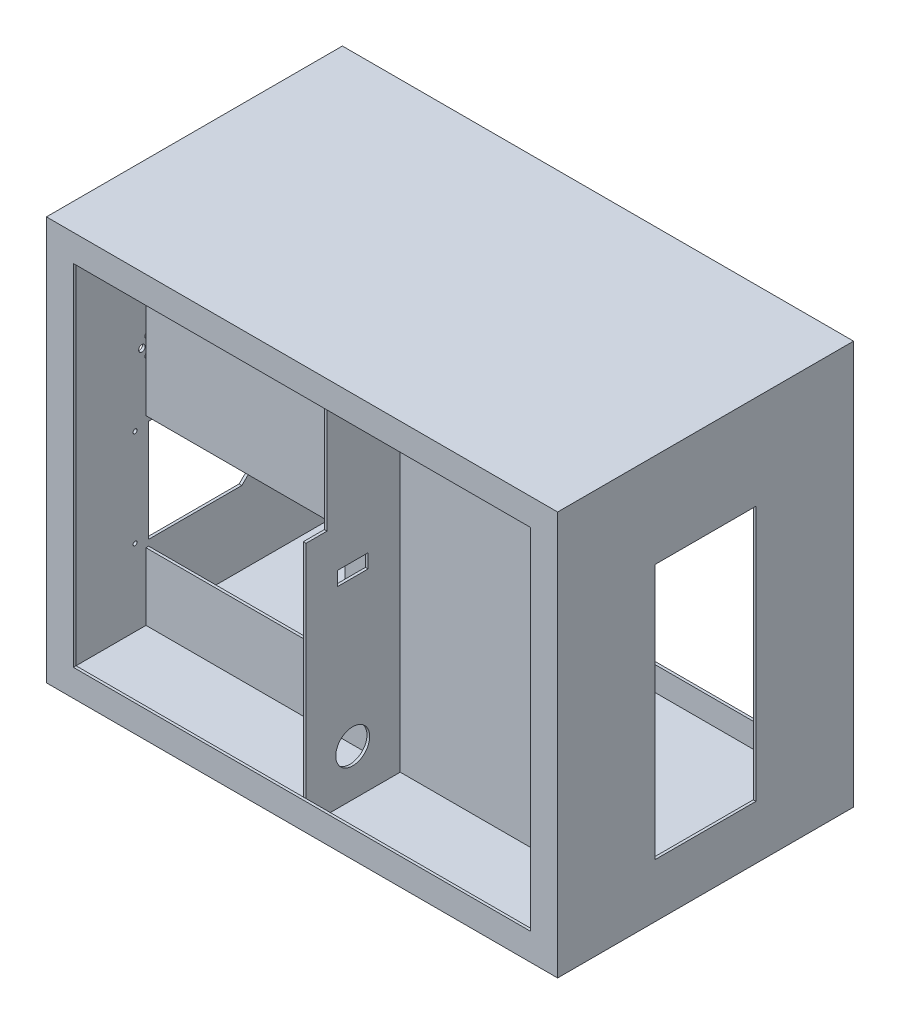
SolidWorks part; units mm, degrees
material "Acero al carbono no aleado"
ref_plane "Alzado" through (0, 0, 0) normal (0, 0, 1) x (1, 0, 0)
ref_plane "Planta" through (0, 0, 0) normal (0, 1, 0) x (1, 0, 0)
ref_plane "Vista lateral" through (0, 0, 0) normal (1, 0, 0) x (0, 0, -1)
sketch "Croquis1" plane through (0, 0, 0) normal (0, 0, 1) x (1, 0, 0)
  line L1 (190, -150) -> (-190, -150)
  line L2 (190, -150) -> (190, 150)
  line L3 (190, 150) -> (-190, 150)
  line L4 (-190, -150) -> (-190, 150)
  line L5 (190, -150) -> (-190, 150) construction
  line L6 (190, 150) -> (-190, -150) construction
  point P0 (0, 0)
  dimension "D1" = 380
  dimension "D2" = 300
extrude "Saliente-Extruir1" add sketch "Croquis1" along normal blind 220
sketch "Croquis2" plane through (0, 0, 220) normal (0, 0, 1) x (1, 0, 0)
  line L1 (-170, -130) -> (170, -130)
  line L2 (-170, -130) -> (-170, 130)
  line L3 (-170, 130) -> (170, 130)
  line L4 (170, -130) -> (170, 130)
  line L5 (-170, -130) -> (170, 130) construction
  line L6 (-170, 130) -> (170, -130) construction
  point P0 (0, 0)
  dimension "D1" = 340
  dimension "D2" = 260
extrude "Cortar-Extruir1" cut sketch "Croquis2" against normal through all
sketch "Croquis3" plane through (190, 0, 0) normal (1, 0, 0) x (0, 0, -1)
  line L0 (-220, -150) -> (0, -150) construction
  line L1 (-147.5, 80) -> (-72.5, 80)
  line L2 (-147.5, 80) -> (-147.5, -110)
  line L3 (-147.5, -110) -> (-72.5, -110)
  line L4 (-72.5, 80) -> (-72.5, -110)
  line L5 (-147.5, 80) -> (-72.5, -110) construction
  line L6 (-147.5, -110) -> (-72.5, 80) construction
  line L7 (-220, 150) -> (0, 150) construction
  point P0 (-110, -15)
  point P8 (-110, -150)
  dimension "D1" = 75
  dimension "D2" = 70
  dimension "D3" = 40
extrude "Cortar-Extruir2" cut sketch "Croquis3" against normal blind 220
sketch "Croquis4" plane through (-190, 0, 0) normal (-1, 0, 0) x (0, 0, 1)
  line L0 (20.7709, 67.1061) -> (23.2287, 61.2188)
  line L1 (22.0366, 127.5153) -> (42.2872, 127.5153)
  line L2 (22.0366, 127.5153) -> (22.0366, 99.6708)
  line L3 (22.0366, 99.6708) -> (42.2872, 99.6708)
  line L4 (42.2872, 127.5153) -> (42.2872, 99.6708)
  line L5 (154.045, 32.5908) -> (133.2882, 68.5426) construction
  line L6 (133.2882, 68.5426) -> (91.7745, 68.5426) construction
  line L7 (91.7745, 68.5426) -> (71.0177, 32.5908) construction
  line L8 (71.0177, 32.5908) -> (91.7745, -3.3611) construction
  line L9 (91.7745, -3.3611) -> (133.2882, -3.3611) construction
  line L10 (133.2882, -3.3611) -> (154.045, 32.5908) construction
  line L11 (23.2287, 61.2188) -> (36.6447, 61.2188)
  line L12 (36.6447, 61.2188) -> (39.8123, 67.1061)
  line L13 (39.8123, 67.1061) -> (20.7709, 67.1061)
  line L14 (71.0177, 64.4261) -> (156.7168, 64.4261) construction
  line L15 (71.0177, 57.9261) -> (156.7168, 57.9261) construction
  line L16 (71.0177, 51.4261) -> (156.7168, 51.4261) construction
  line L17 (71.0177, 44.9261) -> (156.7168, 44.9261) construction
  line L18 (71.0177, 38.4261) -> (156.7168, 38.4261) construction
  line L19 (71.0177, 31.9261) -> (156.7168, 31.9261) construction
  line L20 (71.0177, 25.4261) -> (156.7168, 25.4261) construction
  line L21 (71.0177, 18.9261) -> (156.7168, 18.9261) construction
  line L22 (71.0177, 12.4261) -> (156.7168, 12.4261) construction
  line L23 (71.0177, 5.9261) -> (156.7168, 5.9261) construction
  line L24 (71.0177, -0.5739) -> (156.7168, -0.5739) construction
  line L25 (71.0177, 25.4261) -> (156.7168, 25.4261) construction
  line L26 (71.0177, 18.9261) -> (156.7168, 18.9261) construction
  line L27 (71.0177, 12.4261) -> (156.7168, 12.4261) construction
  line L28 (71.0177, 5.9261) -> (156.7168, 5.9261) construction
  line L29 (71.0177, -0.5739) -> (156.7168, -0.5739) construction
  line L30 (133.2882, -4.6904) -> (91.7745, -4.6904) construction
  line L31 (0, 150) -> (0, -150) construction
  line L33 (16, -25.8535) -> (16, -87.8535)
  line L34 (76.6963, -93.5498) -> (146, -93.5498)
  line L35 (146, -17.5498) -> (146, -93.5498)
  line L37 (16, -25.8535) -> (71, -25.8535) construction
  line L38 (16, -25.8535) -> (16, -87.8535) construction
  line L39 (16, -87.8535) -> (71, -87.8535) construction
  line L40 (71, -25.8535) -> (71, -87.8535) construction
  line L41 (71, -87.8535) -> (76.6963, -93.5498)
  line L42 (71, -25.8535) -> (79.3037, -17.5498)
  line L43 (71, -87.8535) -> (16, -87.8535)
  line L44 (71, -25.8535) -> (16, -25.8535)
  line L45 (79.3037, -17.5498) -> (146, -17.5498)
  circle A0 centre (112.5313, 32.5908) radius 35.9519 construction
  circle A1 centre (32.1622, 10.252) radius 11.3909
  circle A2 centre (89.3978, 64.4261) radius 2.4
  circle A3 centre (85.6451, 57.9261) radius 2.5
  circle A4 centre (81.9084, 51.4261) radius 2.4
  circle A5 centre (78.1395, 44.9261) radius 2.4
  circle A6 centre (74.3867, 38.4261) radius 2.4
  circle A7 centre (71.0177, 31.9261) radius 2.4
  circle A8 centre (97.3978, 64.4261) radius 2.4
  circle A9 centre (105.3978, 64.4261) radius 2.4
  circle A10 centre (113.3978, 64.4261) radius 2.4
  circle A11 centre (121.3978, 64.4261) radius 2.4
  circle A12 centre (129.3978, 64.4261) radius 2.4
  circle A13 centre (93.6451, 57.9261) radius 2.5
  circle A14 centre (101.6451, 57.9261) radius 2.5
  circle A15 centre (109.6451, 57.9261) radius 2.5
  circle A16 centre (117.6451, 57.9261) radius 2.5
  circle A17 centre (125.6451, 57.9261) radius 2.5
  circle A18 centre (133.6451, 57.9261) radius 2.5
  circle A19 centre (89.9084, 51.4261) radius 2.4
  circle A20 centre (97.9084, 51.4261) radius 2.4
  circle A21 centre (105.9084, 51.4261) radius 2.4
  circle A22 centre (113.9084, 51.4261) radius 2.4
  circle A23 centre (121.9084, 51.4261) radius 2.4
  circle A24 centre (129.9084, 51.4261) radius 2.4
  circle A25 centre (137.9084, 51.4261) radius 2.4
  circle A26 centre (86.1395, 44.9261) radius 2.4
  circle A27 centre (94.1395, 44.9261) radius 2.4
  circle A28 centre (102.1395, 44.9261) radius 2.4
  circle A29 centre (110.1395, 44.9261) radius 2.4
  circle A30 centre (118.1395, 44.9261) radius 2.4
  circle A31 centre (126.1395, 44.9261) radius 2.4
  circle A32 centre (134.1395, 44.9261) radius 2.4
  circle A33 centre (142.1395, 44.9261) radius 2.4
  circle A34 centre (82.3867, 38.4261) radius 2.4
  circle A35 centre (90.3867, 38.4261) radius 2.4
  circle A36 centre (98.3867, 38.4261) radius 2.4
  circle A37 centre (106.3867, 38.4261) radius 2.4
  circle A38 centre (114.3867, 38.4261) radius 2.4
  circle A39 centre (122.3867, 38.4261) radius 2.4
  circle A40 centre (130.3867, 38.4261) radius 2.4
  circle A41 centre (138.3867, 38.4261) radius 2.4
  circle A42 centre (146.3867, 38.4261) radius 2.4
  circle A43 centre (79.0177, 31.9261) radius 2.4
  circle A44 centre (87.0177, 31.9261) radius 2.4
  circle A45 centre (95.0177, 31.9261) radius 2.4
  circle A46 centre (103.0177, 31.9261) radius 2.4
  circle A47 centre (111.0177, 31.9261) radius 2.4
  circle A48 centre (119.0177, 31.9261) radius 2.4
  circle A49 centre (127.0177, 31.9261) radius 2.4
  circle A50 centre (135.0177, 31.9261) radius 2.4
  circle A51 centre (143.0177, 31.9261) radius 2.4
  circle A52 centre (151.0177, 31.9261) radius 2.4
  circle A53 centre (146.3867, 25.4261) radius 2.4
  circle A54 centre (138.3867, 25.4261) radius 2.4
  circle A55 centre (130.3867, 25.4261) radius 2.4
  circle A56 centre (122.3867, 25.4261) radius 2.4
  circle A57 centre (114.3867, 25.4261) radius 2.4
  circle A58 centre (106.3867, 25.4261) radius 2.4
  circle A59 centre (98.3867, 25.4261) radius 2.4
  circle A60 centre (90.3867, 25.4261) radius 2.4
  circle A61 centre (82.3867, 25.4261) radius 2.4
  circle A62 centre (142.1395, 18.9261) radius 2.4
  circle A63 centre (134.1395, 18.9261) radius 2.4
  circle A64 centre (126.1395, 18.9261) radius 2.4
  circle A65 centre (118.1395, 18.9261) radius 2.4
  circle A66 centre (110.1395, 18.9261) radius 2.4
  circle A67 centre (102.1395, 18.9261) radius 2.4
  circle A68 centre (94.1395, 18.9261) radius 2.4
  circle A69 centre (86.1395, 18.9261) radius 2.4
  circle A70 centre (137.9084, 12.4261) radius 2.4
  circle A71 centre (129.9084, 12.4261) radius 2.4
  circle A72 centre (121.9084, 12.4261) radius 2.4
  circle A73 centre (113.9084, 12.4261) radius 2.4
  circle A74 centre (105.9084, 12.4261) radius 2.4
  circle A75 centre (97.9084, 12.4261) radius 2.4
  circle A76 centre (89.9084, 12.4261) radius 2.4
  circle A77 centre (133.6451, 5.9261) radius 2.5
  circle A78 centre (125.6451, 5.9261) radius 2.5
  circle A79 centre (117.6451, 5.9261) radius 2.5
  circle A80 centre (109.6451, 5.9261) radius 2.5
  circle A81 centre (101.6451, 5.9261) radius 2.5
  circle A82 centre (93.6451, 5.9261) radius 2.5
  circle A83 centre (129.3978, -0.5739) radius 2.4
  circle A84 centre (121.3978, -0.5739) radius 2.4
  circle A85 centre (113.3978, -0.5739) radius 2.4
  circle A86 centre (105.3978, -0.5739) radius 2.4
  circle A87 centre (97.3978, -0.5739) radius 2.4
  circle A88 centre (74.3867, 25.4261) radius 2.4
  circle A89 centre (78.1395, 18.9261) radius 2.4
  circle A90 centre (81.9084, 12.4261) radius 2.4
  circle A91 centre (85.6451, 5.9261) radius 2.5
  circle A92 centre (89.3978, -0.5739) radius 2.4
  circle A93 centre (156.1, -91.158) radius 1.5
  circle A94 centre (20.1, -91.158) radius 1.5
  circle A95 centre (20.1, -19) radius 1.5
  circle A96 centre (156.1, -19) radius 1.5
  dimension "D2" = 6
  dimension "D1" = 76
  dimension "D9" = 16
  dimension "D10" = 62
  dimension "D11" = 55
  dimension "D3" = 7
  dimension "D4" = 8
  dimension "D5" = 9
  dimension "D6" = 10
  dimension "D7" = 11
extrude "Cortar-Extruir3" cut sketch "Croquis4" against normal blind 10
ref_plane "Plano1" through (0, 0, 2) normal (0, 0, 1) x (1, 0, 0)
sketch "Croquis5" plane through (0, 0, 2) normal (0, 0, 1) x (1, 0, 0)
  line L0 (190, 150) -> (-190, 150) construction
  line L1 (188, -148) -> (-188, -148)
  line L2 (188, -148) -> (188, 148)
  line L3 (188, 148) -> (-188, 148)
  line L4 (-188, -148) -> (-188, 148)
  line L5 (188, -148) -> (-188, 148) construction
  line L6 (188, 148) -> (-188, -148) construction
  line L7 (-190, 150) -> (-190, -150) construction
  point P0 (0, 0)
  dimension "D1" = 2
  dimension "D2" = 2
extrude "Cortar-Extruir4" cut sketch "Croquis5" along normal blind 216
ref_plane "Plano2" through (0, 0, 146) normal (0, 0, 1) x (1, 0, 0)
sketch "Croquis6" plane through (0, 0, 146) normal (0, 0, 1) x (1, 0, 0)
  line L1 (-190, -98) -> (-40, -98)
  line L2 (-190, -98) -> (-190, -13)
  line L3 (-190, -13) -> (-40, -13)
  line L4 (-188, 148) -> (-188, -148)
  line L5 (-188, -148) -> (188, -148)
  line L6 (188, -148) -> (188, 148)
  line L7 (188, 148) -> (-188, 148)
  line L8 (-188, 148) -> (-188, -148)
  line L9 (-188, -148) -> (188, -148)
  line L10 (188, -148) -> (188, 148)
  line L11 (188, 148) -> (-188, 148)
  line L12 (-40, -98) -> (-40, -13)
  circle A0 centre (-40, 123.2299) radius 11.3077
  circle A1 centre (-40, 89.4403) radius 12.0766
  dimension "D2" = 85
  dimension "D3" = 150
  dimension "D4" = 50
  dimension "D1" = 0
extrude "Saliente-Extruir2" add sketch "Croquis6" along normal blind 2 contours L12 L1 L8 L9 L10 L11 L3
ref_plane "Plano3" through (0, 0, 0) normal (-1, 0, 0) x (0, 0, 1)
sketch "Croquis7" plane through (0, 0, 0) normal (-1, 0, 0) x (0, 0, 1)
  line L1 (218, 134.4822) -> (202.4348, 134.4822)
  line L2 (218, 134.4822) -> (218, 34.4024)
  line L3 (218, 34.4024) -> (202.4348, 34.4024)
  line L4 (148, 148) -> (148, -148)
  line L5 (148, -148) -> (218, -148)
  line L6 (218, -148) -> (218, 148)
  line L7 (218, 148) -> (148, 148)
  line L8 (148, 148) -> (148, -148)
  line L9 (148, -148) -> (218, -148)
  line L10 (218, -148) -> (218, 148)
  line L11 (218, 148) -> (148, 148)
  line L12 (202.4348, 134.4822) -> (202.4348, 34.4024)
  line L13 (194.7898, 5.2125) -> (171.8549, 5.2125)
  line L14 (194.7898, 5.2125) -> (194.7898, -5.2125)
  line L15 (194.7898, -5.2125) -> (171.8549, -5.2125)
  line L16 (171.8549, 5.2125) -> (171.8549, -5.2125)
  circle A0 centre (183.3223, -113.6323) radius 12.5918
  dimension "D1" = 0
extrude "Saliente-Extruir3" add sketch "Croquis7" along normal mid plane 2 contours L12 L1 L10 L11 L8 L9 L3 A0 L16 L13 L14 L15
